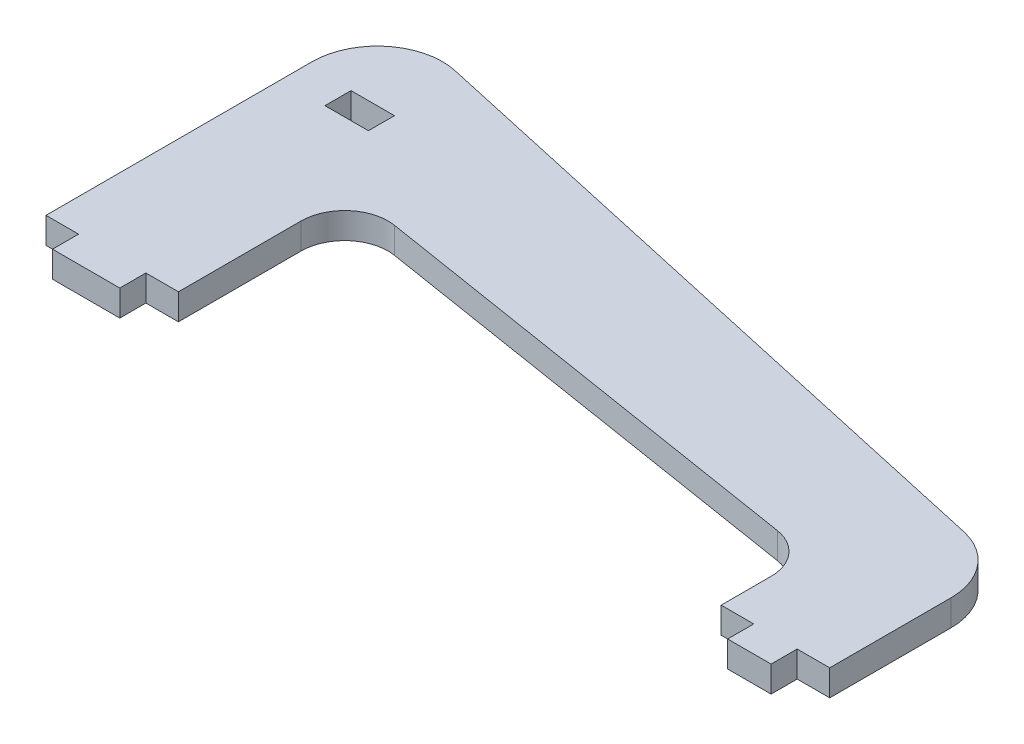
SolidWorks part; units mm, degrees
ref_plane "Front Plane" through (0, 0, 0) normal (0, 0, 1) x (1, 0, 0)
ref_plane "Top Plane" through (0, 0, 0) normal (0, 1, 0) x (1, 0, 0)
ref_plane "Right Plane" through (0, 0, 0) normal (1, 0, 0) x (0, 0, -1)
sketch "Sketch1" plane through (0, 0, 0) normal (0, 1, 0) x (1, 0, 0)
  line L3 (0, 9.7222) -> (-7.5, 9.7222)
  line L4 (10, 9.7222) -> (17.5, 9.7222)
  line L5 (-7.5, 9.7222) -> (-7.5, 21.195)
  line L7 (17.5, 9.7222) -> (17.5, 37.6824)
  line L9 (-132.5, 37.995) -> (-132.5, 9.7222)
  line L10 (-132.5, 9.7222) -> (-140, 9.7222)
  line L14 (-155.5, 9.7222) -> (-163, 9.7222)
  line L15 (-163, 9.7222) -> (-163, 71.0342)
  line L16 (5.7454, 52.3271) -> (-144.7546, 85.6789)
  line L17 (-15.9201, 31.0694) -> (-120.9201, 47.8694)
  line L18 (-147.75, 3.7222) -> (-147.75, 63.7222) construction
  line L20 (-140, 9.7222) -> (-140, 3.7222)
  line L21 (-140, 3.7222) -> (-155.5, 3.7222)
  line L22 (-155.5, 3.7222) -> (-155.5, 9.7222)
  line L23 (0, 9.7222) -> (0, 3.7222)
  line L24 (0, 3.7222) -> (10, 3.7222)
  line L25 (10, 3.7222) -> (10, 9.7222)
  line L27 (-152.75, 63.7222) -> (-142.75, 63.7222)
  line L29 (-142.75, 63.7222) -> (-142.75, 69.7222)
  line L30 (-142.75, 69.7222) -> (-152.75, 69.7222)
  line L31 (-152.75, 69.7222) -> (-152.75, 63.7222)
  arc A0 (17.5, 37.6824) -> (5.7454, 52.3271) centre (2.5, 37.6824) ccw
  arc A1 (-7.5, 21.195) -> (-15.9201, 31.0694) centre (-17.5, 21.195) ccw
  arc A2 (-120.9201, 47.8694) -> (-132.5, 37.995) centre (-122.5, 37.995) ccw
  arc A3 (-163, 71.0342) -> (-144.7546, 85.6789) centre (-148, 71.0342) cw
  point P19 (17.5, 49.7222)
  point P22 (-7.5, 29.7222)
  point P25 (-132.5, 49.7222)
  point P28 (-163, 89.7222)
  point P33 (-147.75, 63.7222)
  dimension "D12" = 15
  dimension "D13" = 10
  dimension "D14" = 10
  dimension "D15" = 15
  dimension "D1" = 140
  dimension "D2" = 6
  dimension "D3" = 6
  dimension "D4" = 7.5
  dimension "D5" = 7.5
  dimension "D6" = 7.5
  dimension "D7" = 7.5
  dimension "D8" = 40
  dimension "D9" = 80
  dimension "D10" = 20
  dimension "D11" = 40
  dimension "D16" = 10
  dimension "D17" = 60
  dimension "D18" = 10
  dimension "D19" = 15.5
  dimension "D20" = 6
extrude "Boss-Extrude1" add sketch "Sketch1" along normal blind 6
